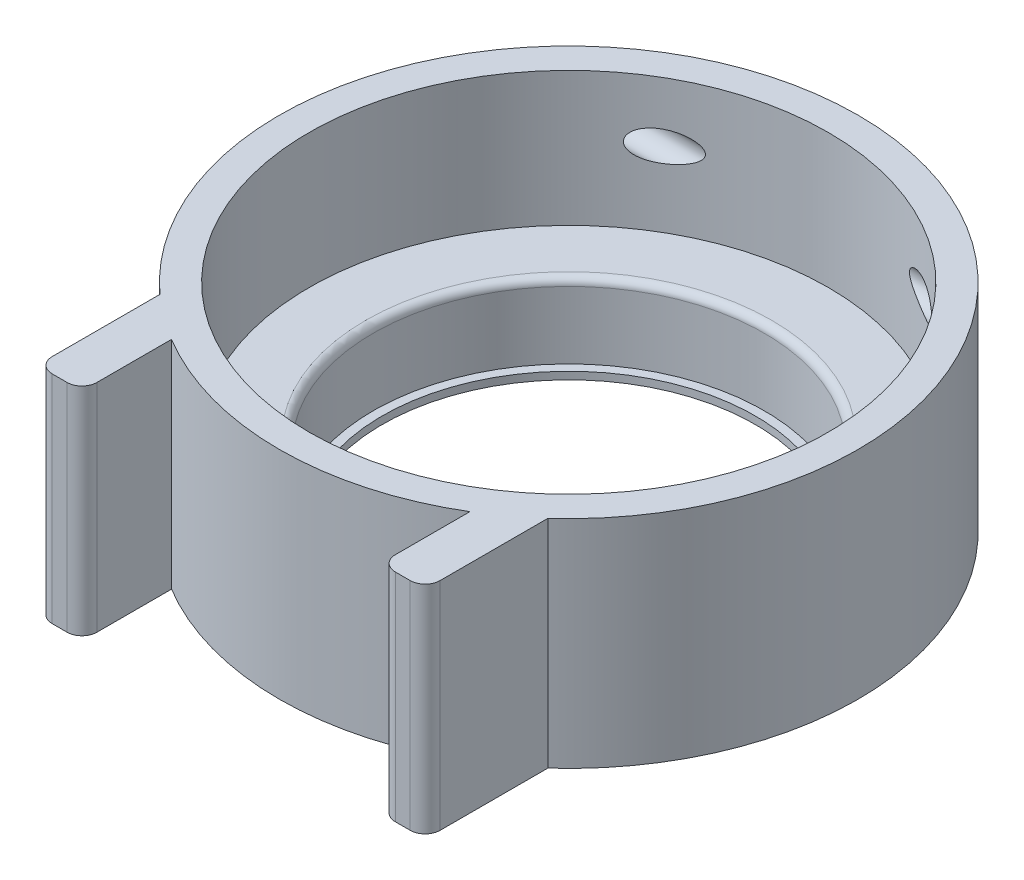
SolidWorks part; units mm, degrees
ref_plane "前视基准面" through (0, 0, 0) normal (0, 0, 1) x (1, 0, 0)
ref_plane "上视基准面" through (0, 0, 0) normal (0, 1, 0) x (1, 0, 0)
ref_plane "右视基准面" through (0, 0, 0) normal (1, 0, 0) x (0, 0, -1)
other "Configuration Table"
sketch "草图1" plane through (0, 0, 0) normal (0, 1, 0) x (1, 0, 0)
  circle A0 centre (0, 0) radius 17.4
  dimension "D1" = 34.8
extrude "拉伸-薄壁1" add sketch "草图1" along normal blind 14.5 thin
sketch "草图2" plane through (0, 0, 0) normal (0, 1, 0) x (1, 0, 0)
  circle A0 centre (0, 0) radius 17.5
  circle A1 centre (0, 0) radius 13.1
  dimension "D1" = 35
  dimension "D2" = 26.2
extrude "凸台-拉伸1" add sketch "草图2" along normal blind 5.5
sketch "草图3" plane through (0, 0, 0) normal (0, 1, 0) x (1, 0, 0)
  circle A0 centre (0, 0) radius 13.1
  circle A1 centre (0, 0) radius 12.5
  dimension "D1" = 26.2
  dimension "D2" = 25
extrude "凸台-拉伸2" add sketch "草图3" along normal blind 0.5
sketch "草图4" plane through (0, 0, 0) normal (0, 1, 0) x (1, 0, 0)
  line L0 (0, 0) -> (0, -27.8008) construction
  line L1 (-13, -14.4) -> (-13, -22.6241)
  line L2 (-13, -22.6241) -> (-10, -22.6241)
  line L3 (-10, -22.6241) -> (-10, -16.6241)
  line L4 (10, -22.6241) -> (10, -16.6241)
  line L5 (13, -22.6241) -> (10, -22.6241)
  line L6 (13, -14.4) -> (13, -22.6241)
  circle A0 centre (0, 0) radius 19.4 construction
  circle A1 centre (0, 0) radius 19.4
  dimension "D1" = 3
  dimension "D2" = 10
  dimension "D3" = 6
extrude "凸台-拉伸3" add sketch "草图4" along normal up to surface (14.5 mm away) contours A1 L1 L2 L3 | A1 L4 L5 L6 up to face at (19.4, 14.5, 0)
sketch "草图6" plane through (0, 0, 0) normal (1, 0, 0) x (0, 0, -1)
  line L0 (-14.4, 0) -> (19.4, 0) construction
  circle A0 centre (15, 10.5) radius 1
  dimension "D1" = 2
  dimension "D2" = 10.5
  dimension "D3" = 15
extrude "切除-拉伸1" cut sketch "草图6" against normal through all both and the other way through all
fillet "圆角1" radius 1 4 edges at (10, 7.25, 22.6241) (-10, 7.25, 22.6241) (13, 7.25, 22.6241) (-13, 7.25, 22.6241)
fillet "圆角2" radius 0.5 1 edges at (0, 5.5, 13.1)
